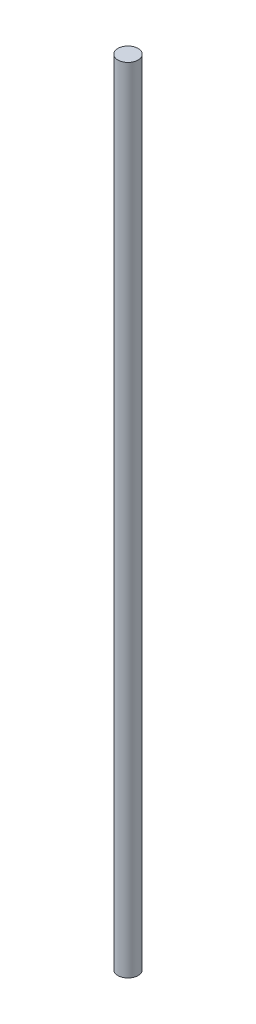
SolidWorks part; units mm, degrees
ref_plane "Front Plane" through (0, 0, 0) normal (0, 0, 1) x (1, 0, 0)
ref_plane "Top Plane" through (0, 0, 0) normal (0, 1, 0) x (1, 0, 0)
ref_plane "Right Plane" through (0, 0, 0) normal (1, 0, 0) x (0, 0, -1)
sketch "Sketch1" plane through (0, 0, 0) normal (0, 1, 0) x (1, 0, 0)
  circle A0 centre (0, 0) radius 4
  dimension "D1" = 8
extrude "Boss-Extrude1" add sketch "Sketch1" along normal blind 315
